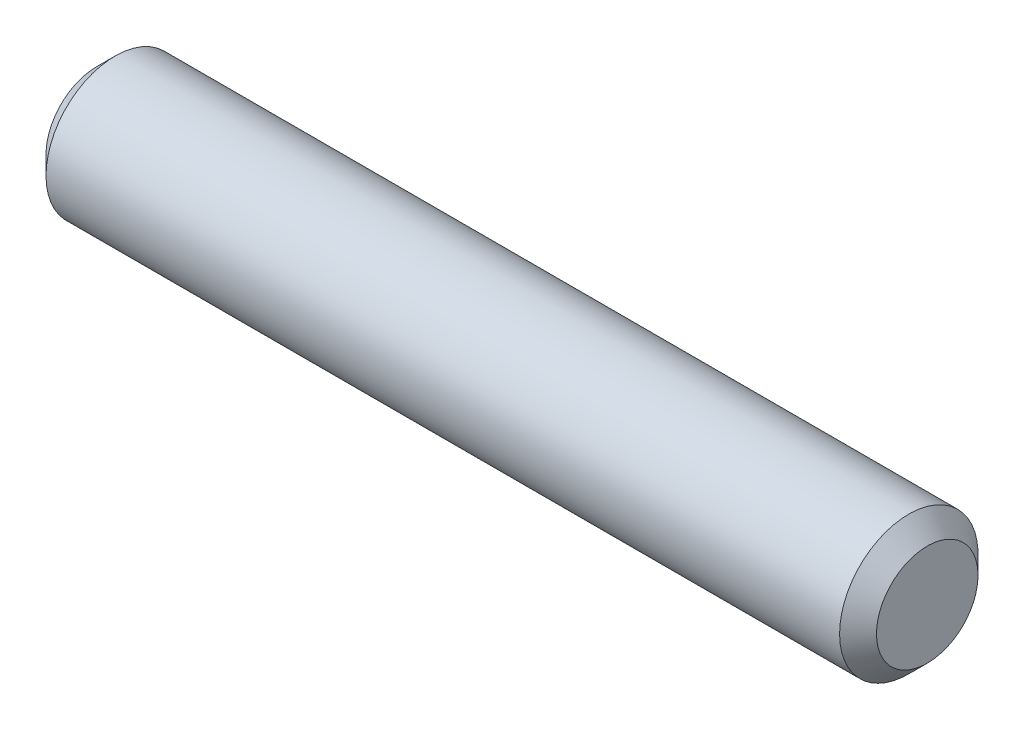
SolidWorks part; units mm, degrees
ref_plane "Front Plane" through (0, 0, 0) normal (0, 0, 1) x (1, 0, 0)
ref_plane "Top Plane" through (0, 0, 0) normal (0, 1, 0) x (1, 0, 0)
ref_plane "Right Plane" through (0, 0, 0) normal (1, 0, 0) x (0, 0, -1)
sketch "Sketch1" plane through (0, 0, 0) normal (0, 0, 1) x (1, 0, 0)
  line L0 (-7.1938, -1.9464) -> (1.8062, -1.9464)
  line L1 (-6.9938, -2.6964) -> (1.6062, -2.6964)
  line L2 (-7.1938, -1.9464) -> (-7.1938, -2.4964)
  line L3 (1.8062, -1.9464) -> (1.8062, -2.4964)
  line L4 (-7.1938, -2.6964) -> (1.8062, -2.6964) construction
  line L5 (-7.1938, -2.4964) -> (-6.9938, -2.6964)
  line L6 (1.6062, -2.6964) -> (1.8062, -2.4964)
  dimension "D2" = 0.75
revolve "Revolve1" add sketch "Sketch1" angle 360 about L0
